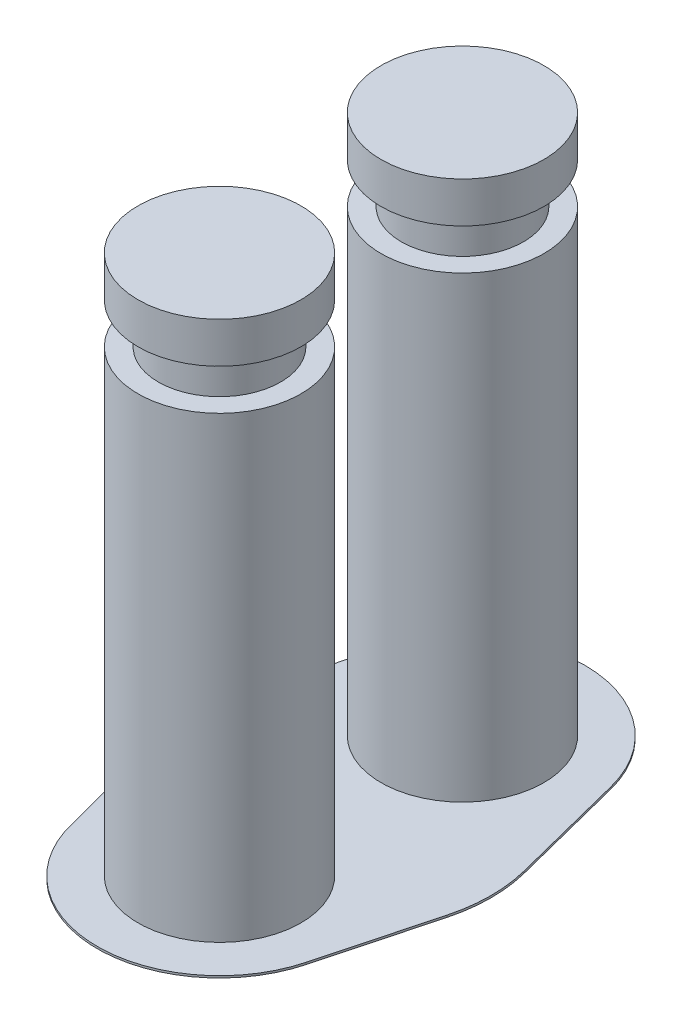
SolidWorks part; units mm, degrees
ref_plane "Front Plane" through (0, 0, 0) normal (0, 0, 1) x (1, 0, 0)
ref_plane "Top Plane" through (0, 0, 0) normal (0, 1, 0) x (1, 0, 0)
ref_plane "Right Plane" through (0, 0, 0) normal (1, 0, 0) x (0, 0, -1)
sketch "Sketch2" plane through (0, 0, 0) normal (0, 1, 0) x (1, 0, 0)
  line L0 (3.75, 7.5) -> (3.75, -7.5) construction
  line L1 (-3.4934, -1.9449) -> (-1.9217, -7.7985)
  line L2 (10.9985, -1.9261) -> (9.5488, -7.3818)
  line L3 (11.0189, 1.8474) -> (9.5651, 7.5676)
  line L4 (-2.0651, 7.5676) -> (-3.5189, 1.8474)
  circle A0 centre (7.5, 0) radius 2.5 construction
  circle A1 centre (0, 0) radius 2.5 construction
  circle A2 centre (3.75, 0) radius 7.5
  circle A3 centre (3.75, 6.0897) radius 4 construction
  circle A4 centre (3.75, -5.841) radius 4 construction
  circle A5 centre (3.75, 6.0897) radius 6
  circle A6 centre (3.75, -5.841) radius 6
  dimension "D1" = 7.5
  dimension "D2" = 5
  dimension "D4" = 15
  dimension "D5" = 12
  dimension "D6" = 12
  dimension "D7" = 8
  dimension "D8" = 8
  dimension "D3" = 3.75
extrude "Boss-Extrude2" add sketch "Sketch2" along normal blind 0.1 contours A2 A6 A0 A5 A1 | A6 A2 L1 | A6 A2 A5 A0 | A6 L2 A2 | A6 A1 A5 A2 | A6 A2 L1 | A6 A0 A5 | A5 A6 | A6 A5 A1 | A6 A5 A0 A2 A1 | A2 A5 | A5 A2 L3 | A5 L4 A2
sketch "Sketch3" plane through (0, 0.1, 0) normal (0, 1, 0) x (1, 0, 0)
  line L0 (3.75, -11.841) -> (3.75, 12.0897) construction
  line L1 (-3.7498, -0.0504) -> (11.2499, -0.0406) construction
  circle A0 centre (3.75, -5.841) radius 4
  circle A1 centre (3.75, 6.0897) radius 4
  arc A2 (-1.9217, -7.7985) -> (9.5488, -7.3818) centre (3.75, -5.841) ccw construction
  arc A3 (9.5651, 7.5676) -> (-2.0651, 7.5676) centre (3.75, 6.0897) ccw construction
  arc A4 (-3.5189, 1.8474) -> (-3.4934, -1.9449) centre (3.75, 0) ccw construction
  arc A5 (10.9985, -1.9261) -> (11.0189, 1.8474) centre (3.75, 0) ccw construction
  dimension "D1" = 8
extrude "Boss-Extrude3" add sketch "Sketch3" along normal blind 22.5
sketch "Sketch4" plane through (0, 22.6, 0) normal (0, 1, 0) x (1, 0, 0)
  circle A0 centre (3.75, -5.841) radius 3
  circle A1 centre (3.75, 6.0897) radius 3
  circle A2 centre (3.75, -5.841) radius 4 construction
  circle A3 centre (3.75, 6.0897) radius 4 construction
  dimension "D1" = 6
  dimension "D2" = 6
extrude "Boss-Extrude4" add sketch "Sketch4" along normal blind 2
sketch "Sketch5" plane through (0, 24.6, 0) normal (0, 1, 0) x (1, 0, 0)
  circle A0 centre (3.75, -5.841) radius 4
  circle A1 centre (3.75, 6.0897) radius 4
  dimension "D1" = 8
  dimension "D2" = 8
extrude "Boss-Extrude5" add sketch "Sketch5" along normal blind 2
hole_wizard "#6 Clearance Hole1" positions "Sketch6" profile "Sketch7" hole size "#6" standard "ANSI Inch"
sketch "Sketch6" plane through (0, 0.1, 0) normal (0, 1, 0) x (1, 0, 0)
  point P7 (3.75, 6.0897)
  point P10 (3.75, -5.841)
sketch "Sketch7" plane through (3.75, 0.1, -6.0897) normal (1, 0, 0) x (0, 0, 1)
  line L0 (0, 0) -> (0, 0.1)
  line L1 (0, 0.1) -> (1.8986, 0.1)
  line L2 (1.8986, 0.1) -> (1.8986, 0)
  line L5 (1.8986, 0) -> (0, 0)
  line L11 (0, -6.35) -> (0, 107.95) construction
  dimension "Thru Hole Dia." = 3.7973
  dimension "Thru Hole Depth" = 0.1
hole_wizard "#6-32 Tapped Hole1" positions "Sketch10" profile "Sketch11" tap size "#6-32" standard "ANSI Inch"
sketch "Sketch10" plane through (0, 0.1, 0) normal (0, -1, 0) x (-1, 0, 0)
  point P0 (-3.75, -5.841)
  point P3 (-3.75, 6.0897)
sketch "Sketch11" plane through (3.75, 0.1, 5.841) normal (1, 0, 0) x (0, 0, -1)
  line L0 (0, 0) -> (0, 10.2027)
  line L1 (0, 10.2027) -> (1.3525, 9.39)
  line L2 (1.3525, 9.39) -> (1.3525, 0)
  line L5 (1.3525, 0) -> (0, 0)
  line L10 (0, 10.2027) -> (-1.3525, 9.39) construction
  line L11 (0, -6.35) -> (0, 107.95) construction
  dimension "Tap Drill Dia." = 2.7051
  dimension "Tap Drill Depth" = 9.39
  dimension "Drill Angle" = 118
cosmetic thread "Hole Thread1" parameters "D1"=7.01, "D2"=3.5052
cosmetic thread "Hole Thread2" parameters "D1"=7.01, "D2"=3.5052
